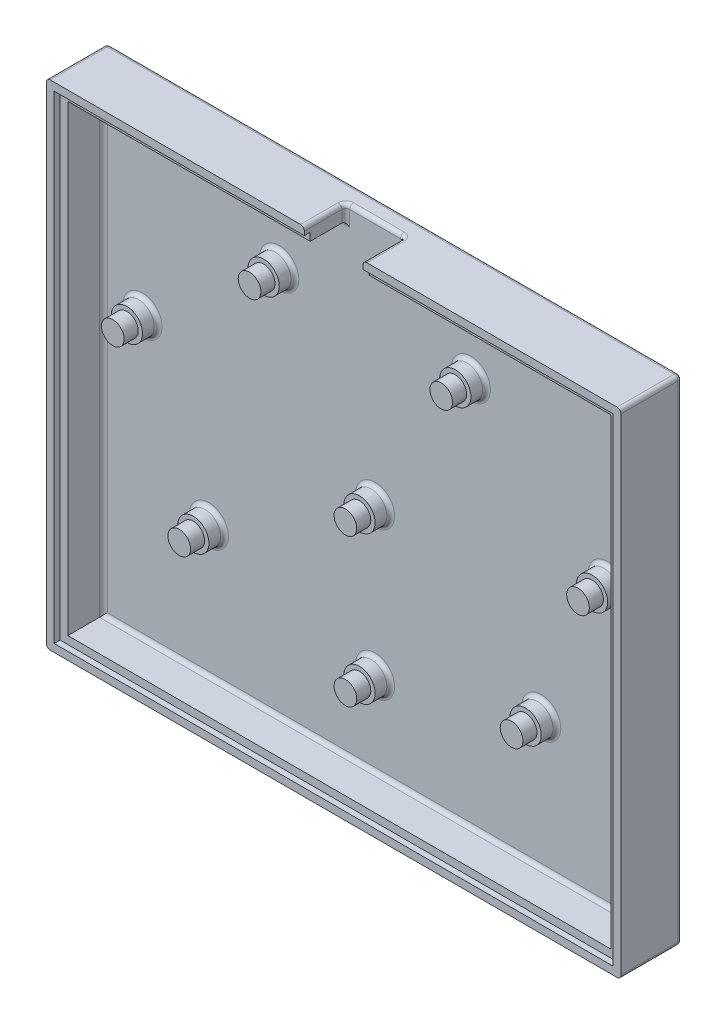
SolidWorks part; units mm, degrees
ref_plane "Alzado" through (0, 0, 0) normal (0, 0, 1) x (1, 0, 0)
ref_plane "Planta" through (0, 0, 0) normal (0, 1, 0) x (1, 0, 0)
ref_plane "Vista lateral" through (0, 0, 0) normal (1, 0, 0) x (0, 0, -1)
sketch "Croquis1" plane through (0, 0, 0) normal (0, 1, 0) x (1, 0, 0)
  line L1 (0, 0) -> (147.05, 0)
  line L2 (0, 0) -> (0, 126.4)
  line L3 (0, 126.4) -> (147.05, 126.4)
  line L4 (147.05, 0) -> (147.05, 126.4)
  dimension "D1" = 126.4
  dimension "D2" = 147.05
extrude "Saliente-Extruir1" add sketch "Croquis1" along normal blind 5
sketch "Croquis2" plane through (0, 5, 0) normal (0, 1, 0) x (1, 0, 0)
  line L8 (4, 122.4) -> (4, 4)
  line L9 (4, 4) -> (143.05, 4)
  line L10 (143.05, 4) -> (143.05, 122.4)
  line L11 (143.05, 122.4) -> (4, 122.4)
  line L12 (4, 122.4) -> (4, 4)
  line L13 (4, 4) -> (143.05, 4)
  line L14 (143.05, 4) -> (143.05, 122.4)
  line L15 (143.05, 122.4) -> (4, 122.4)
  line L16 (0, 126.4) -> (0, 0)
  line L17 (0, 0) -> (147.05, 0)
  line L18 (147.05, 0) -> (147.05, 126.4)
  line L19 (147.05, 126.4) -> (0, 126.4)
  line L20 (0, 126.4) -> (0, 0)
  line L21 (0, 0) -> (147.05, 0)
  line L22 (147.05, 0) -> (147.05, 126.4)
  line L23 (147.05, 126.4) -> (0, 126.4)
  dimension "D1" = 4
  dimension "D2" = 0
extrude "Saliente-Extruir2" add sketch "Croquis2" along normal blind 10.6
sketch "Croquis3" plane through (0, 0, -126.4) normal (0, 0, -1) x (-1, 0, 0)
  line L0 (-147.05, 5) -> (0, 5) construction
  line L2 (-147.05, 15.6) -> (0, 15.6) construction
  line L3 (-147.05, 15.6) -> (-147.05, 0) construction
  line L4 (0, 15.6) -> (0, 0) construction
  line L5 (-147.05, 0) -> (0, 0) construction
  line L6 (-73.525, 15.6) -> (-73.525, 5) construction
  line L7 (-81.025, 5) -> (-66.025, 5)
  line L8 (-81.025, 5) -> (-81.025, 15.6)
  line L9 (-81.025, 15.6) -> (-66.025, 15.6)
  line L10 (-66.025, 5) -> (-66.025, 15.6)
  point P14 (-73.525, 5)
  dimension "D1" = 5
  dimension "D2" = 15
extrude "Cortar-Extruir1" cut sketch "Croquis3" against normal up to surface (4 mm away) up to face at (73.525, 10.3, -122.4)
sketch "Croquis4" plane through (0, 5, 0) normal (0, 1, 0) x (1, 0, 0)
  line L0 (0, 126.4) -> (0, 0) construction
  line L1 (6, 120.4) -> (141.05, 120.4) construction
  line L2 (6, 120.4) -> (6, 6) construction
  line L3 (6, 6) -> (141.05, 6) construction
  line L4 (141.05, 120.4) -> (141.05, 6) construction
  line L5 (147.05, 126.4) -> (81.025, 126.4) construction
  line L6 (0, 0) -> (147.05, 0) construction
  line L7 (147.05, 0) -> (147.05, 126.4) construction
  line L8 (73.525, 120.4) -> (73.525, 6) construction
  circle A0 centre (14, 75.4) radius 4
  circle A1 centre (49, 103.4) radius 4
  circle A2 centre (31, 37.4) radius 4
  circle A3 centre (116.05, 37.4) radius 4
  circle A4 centre (133.05, 75.4) radius 4
  circle A5 centre (98.05, 103.4) radius 4
  circle A6 centre (73.525, 63.2) radius 4
  circle A7 centre (73.525, 25.4) radius 4
  dimension "D7" = 8
  dimension "D8" = 8
  dimension "D11" = 8
  dimension "D14" = 8
  dimension "D1" = 6
  dimension "D2" = 6
  dimension "D3" = 6
  dimension "D4" = 6
  dimension "D5" = 45
  dimension "D6" = 8
  dimension "D9" = 43
  dimension "D10" = 17
  dimension "D12" = 25
  dimension "D13" = 83
  dimension "D15" = 95
ref_plane "Plano1" through (0, 9, 0) normal (0, 1, 0) x (1, 0, 0)
extrude "Saliente-Extruir4" add sketch "Croquis4" along normal blind 4
sketch "Croquis5" plane through (0, 9, 0) normal (0, 1, 0) x (1, 0, 0)
  circle A0 centre (14, 75.4) radius 2.9
  circle A1 centre (49, 103.4) radius 2.9
  circle A2 centre (98.05, 103.4) radius 2.9
  circle A3 centre (73.525, 63.2) radius 2.9
  circle A4 centre (31, 37.4) radius 2.9
  circle A5 centre (116.05, 37.4) radius 2.9
  circle A6 centre (133.05, 75.4) radius 2.9
  circle A7 centre (73.525, 25.4) radius 2.9
  dimension "D1" = 5.8
extrude "Saliente-Extruir5" add sketch "Croquis5" along normal blind 3.6
sketch "Croquis6" plane through (0, 15.6, 0) normal (0, 1, 0) x (1, 0, 0)
  line L27 (66.025, 124.4) -> (81.025, 124.4)
  line L32 (145.05, 124.4) -> (81.025, 124.4)
  line L33 (145.05, 2) -> (145.05, 124.4)
  line L34 (2, 2) -> (145.05, 2)
  line L35 (2, 124.4) -> (2, 2)
  line L36 (66.025, 124.4) -> (2, 124.4)
  line L37 (145.05, 124.4) -> (81.025, 124.4)
  line L38 (145.05, 2) -> (145.05, 124.4)
  line L39 (2, 2) -> (145.05, 2)
  line L40 (2, 124.4) -> (2, 2)
  line L41 (66.025, 124.4) -> (2, 124.4)
  dimension "D1" = 2
extrude "Cortar-Extruir2" cut sketch "Croquis6" against normal blind 1.5
fillet "Redondeo2" radius 1 4 edges at (147.05, 7.8, -126.4) (0, 7.8, -126.4) (147.05, 7.8, 0) (0, 7.8, 0)
move or copy body "Sólido-Mover/Copiar1" bodies to move or copy 108 copy no rotation origin (0, 7.8, -62.2) rotation axis (1, 0, 0) rotation angle 90
fillet "Redondeo3" radius 1 8 edges at (0.2929, 71.7071, -70) (0, 8.8, -70) (0.2929, -54.1071, -70) (73.525, -54.4, -70) (146.7571, -54.1071, -70) (147.05, 8.8, -70) (146.7571, 71.7071, -70) (73.525, 72, -70)
fillet "Redondeo4" radius 1 18 edges at (112.0375, 68, -65) (4, 8.8, -65) (73.525, -50.4, -65) (143.05, 8.8, -65) (35.0125, 68, -65) (81.025, 72, -59.7) (73.525, 72, -65) (66.025, 72, -59.7) (66.025, 70, -65) (81.025, 70, -65) (14, 25, -65) (49, 53, -65) (31, -13, -65) (73.525, -25, -65) (116.05, -13, -65) (133.05, 25, -65) (98.05, 53, -65) (73.525, 12.8, -65)
equation "\"A\"= 6"
equation "\"D2@Croquis4\"=\"A\""
equation "\"D1@Croquis4\"=\"A\""
equation "\"D4@Croquis4\"=\"A\""
equation "\"D3@Croquis4\"=\"A\""
